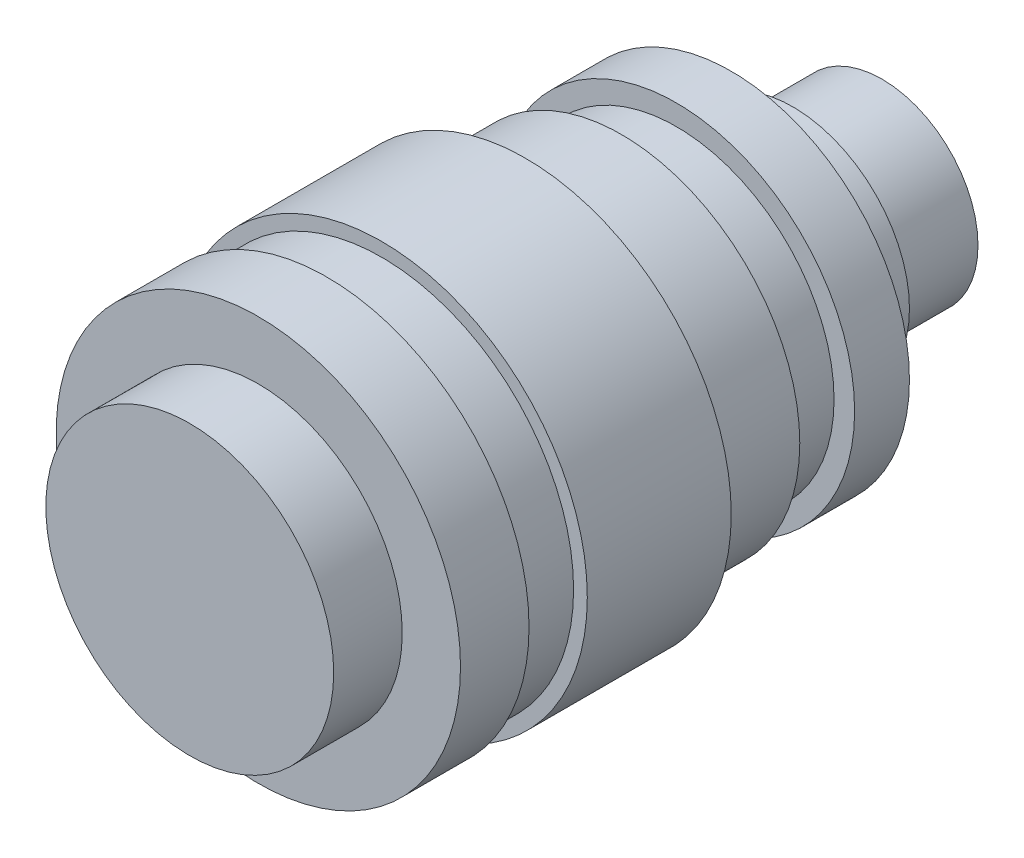
SolidWorks part; units mm, degrees
ref_plane "Front Plane" through (0, 0, 0) normal (0, 0, 1) x (1, 0, 0)
ref_plane "Top Plane" through (0, 0, 0) normal (0, 1, 0) x (1, 0, 0)
ref_plane "Right Plane" through (0, 0, 0) normal (1, 0, 0) x (0, 0, -1)
sketch "Sketch1" plane through (0, 0, 0) normal (1, 0, 0) x (0, 0, -1)
  line L1 (0, 0) -> (5, 0)
  line L2 (0, 0) -> (0, 14.75)
  line L3 (0, 14.75) -> (5, 14.75)
  line L4 (5, 0) -> (5, 14.75)
  line L5 (5, 0) -> (9, 0)
  line L6 (5, 0) -> (5, 14)
  line L7 (5, 14) -> (9, 14)
  line L8 (9, 0) -> (9, 14)
  line L9 (9, 0) -> (19.5, 0)
  line L10 (9, 0) -> (9, 15)
  line L11 (9, 15) -> (19.5, 15)
  line L12 (19.5, 0) -> (19.5, 15)
  line L13 (19.5, 0) -> (26.5, 0)
  line L14 (19.5, 0) -> (19.5, 13)
  line L15 (19.5, 13) -> (26.5, 13)
  line L16 (26.5, 0) -> (26.5, 13)
  line L17 (26.5, 0) -> (30.5, 0)
  line L18 (26.5, 0) -> (26.5, 11.5)
  line L19 (26.5, 11.5) -> (30.5, 11.5)
  line L20 (30.5, 0) -> (30.5, 11.5)
  line L21 (30.5, 0) -> (34.5, 0)
  line L22 (30.5, 0) -> (30.5, 13)
  line L23 (30.5, 13) -> (34.5, 13)
  line L24 (34.5, 0) -> (34.5, 13)
  line L25 (34.5, 0) -> (39, 0)
  line L26 (34.5, 0) -> (34.5, 8.5)
  line L27 (34.5, 8.5) -> (39, 8.5)
  line L28 (39, 0) -> (39, 8.5)
  line L29 (39, 0) -> (45.5, 0)
  line L30 (39, 0) -> (39, 7)
  line L31 (39, 7) -> (45.5, 7)
  line L32 (45.5, 0) -> (45.5, 7)
  line L33 (0, 0) -> (-5, 0)
  line L34 (0, 0) -> (0, 10.5)
  line L35 (0, 10.5) -> (-5, 10.5)
  line L36 (-5, 0) -> (-5, 10.5)
  dimension "D1" = 5
  dimension "D2" = 10.5
  dimension "D3" = 4
  dimension "D4" = 14
  dimension "D5" = 15
  dimension "D6" = 10.5
  dimension "D7" = 13
  dimension "D8" = 7
  dimension "D9" = 4
  dimension "D10" = 11.5
  dimension "D11" = 4
  dimension "D12" = 13
  dimension "D13" = 4.5
  dimension "D14" = 8.5
  dimension "D15" = 7
  dimension "D16" = 6.5
  dimension "D17" = 5
  dimension "D18" = 14.75
revolve "Revolve1" add sketch "Sketch1" angle 360 about L9
